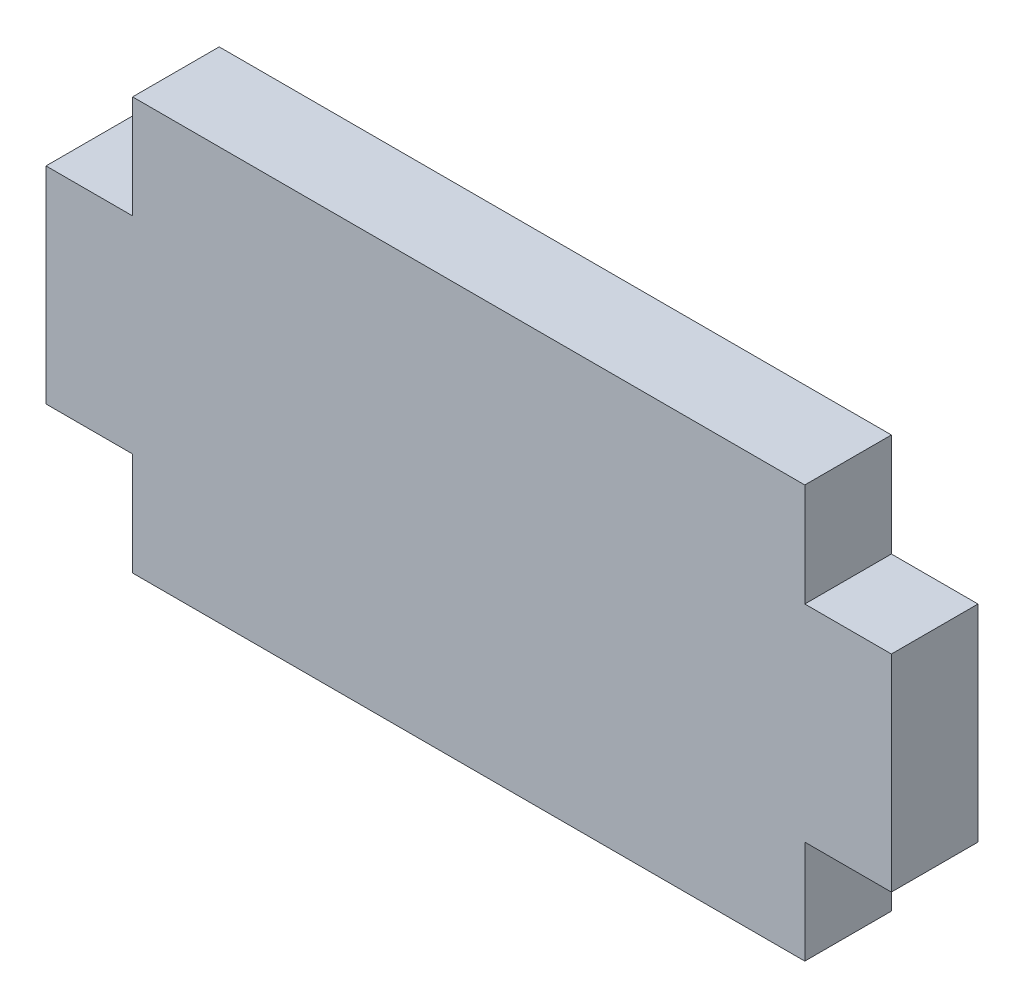
SolidWorks part; units mm, degrees
ref_plane "Front Plane" through (0, 0, 0) normal (0, 0, 1) x (1, 0, 0)
ref_plane "Top Plane" through (0, 0, 0) normal (0, 1, 0) x (1, 0, 0)
ref_plane "Right Plane" through (0, 0, 0) normal (1, 0, 0) x (0, 0, -1)
sketch "Sketch1" plane through (0, 0, 0) normal (0, 0, 1) x (1, 0, 0)
  line L1 (-112.8408, 6.6833) -> (-60.7708, 6.6833)
  line L2 (-112.8408, 6.6833) -> (-112.8408, -18.7167)
  line L3 (-112.8408, -18.7167) -> (-60.7708, -18.7167)
  line L4 (-60.7708, 6.6833) -> (-60.7708, -18.7167)
  dimension "D1" = 25.4
  dimension "D2" = 52.07
extrude "Boss-Extrude1" add sketch "Sketch1" along normal blind 5.334
sketch "Sketch2" plane through (0, 0, 5.334) normal (0, 0, 1) x (1, 0, 0)
  line L1 (-66.1048, -18.7167) -> (-66.1048, -12.3667)
  line L2 (-112.8408, 6.6833) -> (-107.5068, 6.6833)
  line L3 (-112.8408, 6.6833) -> (-112.8408, 0.3333)
  line L4 (-112.8408, 0.3333) -> (-107.5068, 0.3333)
  line L5 (-107.5068, 6.6833) -> (-107.5068, 0.3333)
  line L7 (-60.7708, 6.6833) -> (-112.8408, 6.6833) construction
  line L9 (-112.8408, -18.7167) -> (-107.5068, -18.7167)
  line L10 (-112.8408, -18.7167) -> (-60.7708, -18.7167) construction
  line L11 (-86.8058, 6.6833) -> (-86.8058, -18.7167) construction
  line L12 (-112.8408, -18.7167) -> (-112.8408, -12.3667)
  line L13 (-112.8408, -12.3667) -> (-107.5068, -12.3667)
  line L14 (-107.5068, -18.7167) -> (-107.5068, -12.3667)
  line L15 (-60.7708, -12.3667) -> (-66.1048, -12.3667)
  line L16 (-60.7708, -18.7167) -> (-60.7708, -12.3667)
  line L17 (-60.7708, -18.7167) -> (-66.1048, -18.7167)
  line L18 (-66.1048, 6.6833) -> (-66.1048, 0.3333)
  line L19 (-60.7708, 0.3333) -> (-66.1048, 0.3333)
  line L20 (-60.7708, 6.6833) -> (-60.7708, 0.3333)
  line L21 (-60.7708, 6.6833) -> (-66.1048, 6.6833)
  dimension "D1" = 5.334
  dimension "D2" = 6.35
  dimension "D3" = 6.35
  dimension "D4" = 5.334
extrude "Cut-Extrude1" cut sketch "Sketch2" against normal through all
equation "\"MDF\"= .21in"
equation "\"Foamcore\"= .13in"
equation "\"Gmaterial\"= \"MDF\""
equation "\"D1@Boss-Extrude1\"=\"MDF\""
equation "\"D1@Sketch2\"=\"MDF\""
equation "\"D4@Sketch2\"=\"MDF\""
